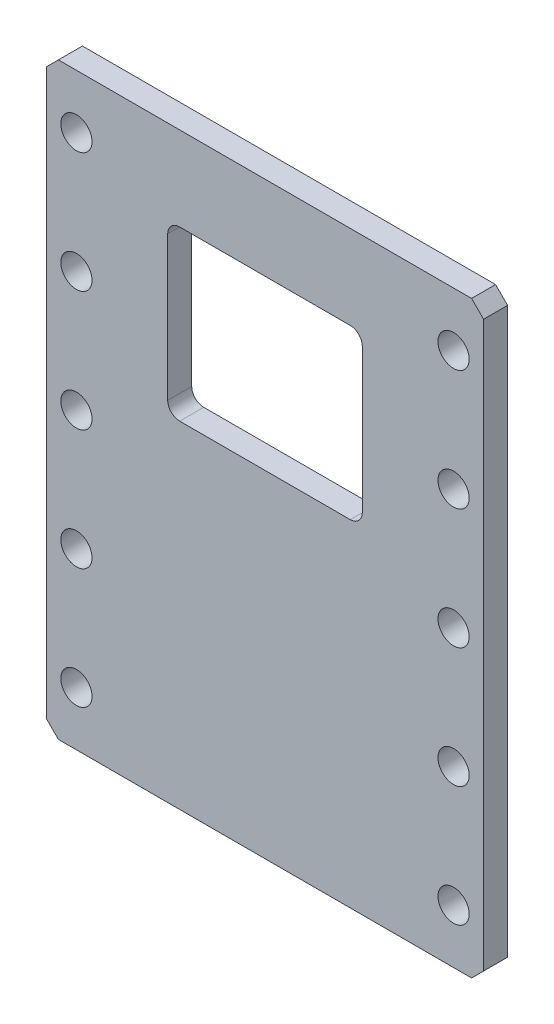
SolidWorks part; units mm, degrees
ref_plane "前视基准面" through (0, 0, 0) normal (0, 0, 1) x (1, 0, 0)
ref_plane "上视基准面" through (0, 0, 0) normal (0, 1, 0) x (1, 0, 0)
ref_plane "右视基准面" through (0, 0, 0) normal (1, 0, 0) x (0, 0, -1)
sketch "草图1" plane through (0, 0, 0) normal (0, 0, 1) x (1, 0, 0)
  line L1 (-182, 245) -> (182, 245)
  line L2 (-182, 245) -> (-182, -245)
  line L3 (-182, -245) -> (182, -245)
  line L4 (182, 245) -> (182, -245)
  line L5 (-182, 245) -> (182, -245) construction
  line L6 (-182, -245) -> (182, 245) construction
  point P0 (0, 0)
  dimension "D1" = 364
  dimension "D2" = 490
extrude "凸台-拉伸1" add sketch "草图1" along normal blind 20
sketch "草图2" plane through (0, 0, 20) normal (0, 0, 1) x (1, 0, 0)
  line L0 (0, 0) -> (0, -132.89) construction
  line L1 (-71, 175) -> (71, 175)
  line L2 (-81, 165) -> (-81, 45)
  line L3 (-71, 35) -> (71, 35)
  line L4 (81, 165) -> (81, 45)
  line L5 (182, 245) -> (-182, 245) construction
  line L6 (-182, 245) -> (-182, -245) construction
  circle A0 centre (-157, 200) radius 13
  circle A1 centre (-157, 100) radius 13
  circle A2 centre (-157, 0) radius 13
  circle A3 centre (-157, -100) radius 13
  circle A4 centre (-157, -200) radius 13
  circle A5 centre (157, -200) radius 13
  circle A6 centre (157, -100) radius 13
  circle A7 centre (157, 0) radius 13
  circle A8 centre (157, 100) radius 13
  circle A9 centre (157, 200) radius 13
  arc A10 (-81, 45) -> (-71, 35) centre (-71, 45) ccw
  arc A11 (71, 35) -> (81, 45) centre (71, 45) ccw
  arc A12 (71, 175) -> (81, 165) centre (71, 165) cw
  arc A13 (-71, 175) -> (-81, 165) centre (-71, 165) ccw
  point P31 (-81, 35)
  point P34 (81, 35)
  point P37 (81, 175)
  dimension "D1" = 26
  dimension "D2" = 26
  dimension "D3" = 26
  dimension "D4" = 26
  dimension "D5" = 26
  dimension "D10" = 10
  dimension "D11" = 25
  dimension "D12" = 45
  dimension "D13" = 100
  dimension "D14" = 100
  dimension "D15" = 100
  dimension "D16" = 100
  dimension "D6" = 162
  dimension "D7" = 140
  dimension "D8" = 70
  dimension "D9" = 81
extrude "切除-拉伸1" cut sketch "草图2" against normal through all
chamfer "倒角1" distance 10 angle 45 4 edges at (-182, -245, 10) (182, -245, 10) (-182, 245, 10) (182, 245, 10)
